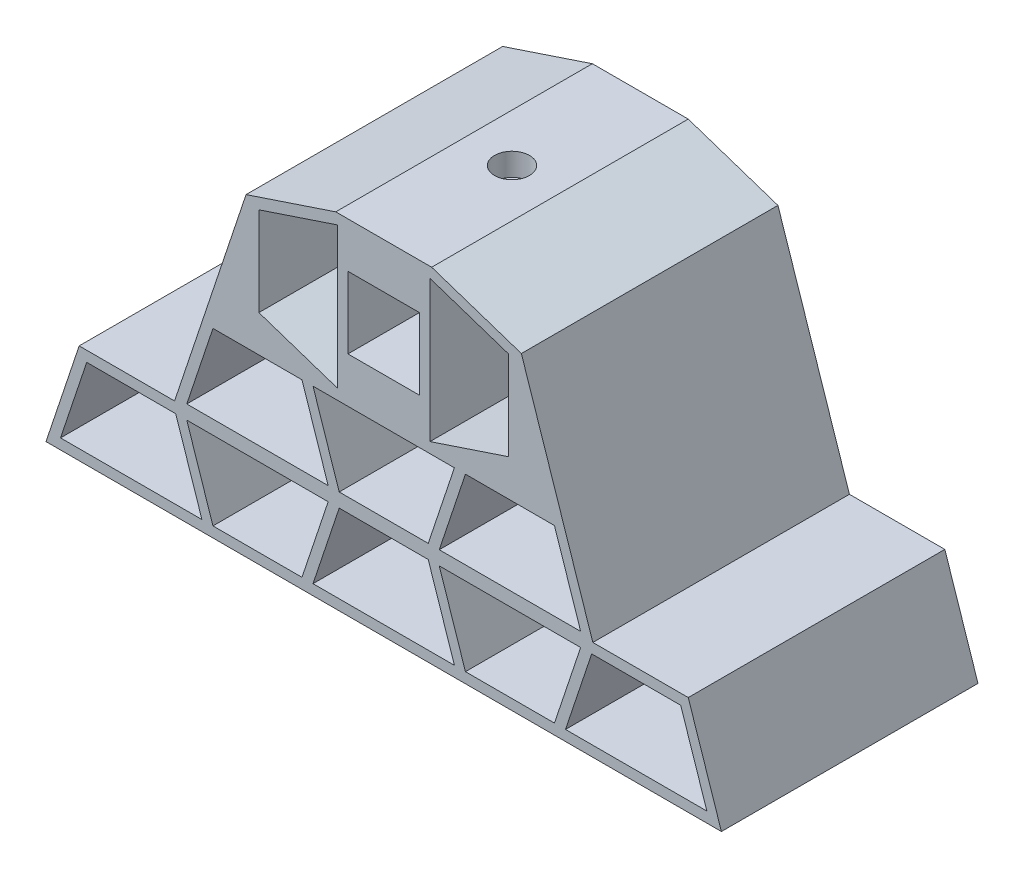
SolidWorks part; units mm, degrees
ref_plane "Front Plane" through (0, 0, 0) normal (0, 0, 1) x (1, 0, 0)
ref_plane "Top Plane" through (0, 0, 0) normal (0, 1, 0) x (1, 0, 0)
ref_plane "Right Plane" through (0, 0, 0) normal (1, 0, 0) x (0, 0, -1)
sketch "Sketch1" plane through (0, 0, 0) normal (0, 0, 1) x (1, 0, 0)
  line L0 (0, 37.8111) -> (0, -97.9817) construction
  line L1 (-53.0722, 0) -> (46.9222, 0) construction
  line L2 (-13.25, 20.25) -> (-13.25, -20.25)
  line L3 (-10.25, -10.25) -> (10.25, -10.25)
  line L4 (-10.25, -10.25) -> (-10.25, 10.25)
  line L5 (-10.25, 10.25) -> (10.25, 10.25)
  line L6 (10.25, -10.25) -> (10.25, 10.25)
  line L7 (-10.25, -10.25) -> (10.25, 10.25) construction
  line L8 (-10.25, 10.25) -> (10.25, -10.25) construction
  line L9 (-13.25, 20.25) -> (-35.75, 12.75)
  line L10 (-35.75, 12.75) -> (-35.75, -12.75)
  line L11 (-13.25, -20.25) -> (-35.75, -12.75)
  line L12 (13.25, -20.25) -> (35.75, -12.75)
  line L13 (35.75, 12.75) -> (35.75, -12.75)
  line L14 (13.25, 20.25) -> (35.75, 12.75)
  line L15 (13.25, 20.25) -> (13.25, -20.25)
  line L31 (-87.2368, -46.75) -> (-59.9079, -46.75)
  line L32 (-99.4186, -49.75) -> (117.8483, -49.75) construction
  line L45 (-12.75, -49.75) -> (12.75, -49.75)
  line L46 (12.75, -49.75) -> (20.25, -72.25)
  line L47 (20.25, -72.25) -> (-20.25, -72.25)
  line L48 (-20.25, -72.25) -> (-12.75, -49.75)
  line L49 (15.9123, -49.75) -> (23.4123, -72.25)
  line L50 (23.4123, -72.25) -> (48.9123, -72.25)
  line L51 (48.9123, -72.25) -> (56.4123, -49.75)
  line L52 (56.4123, -49.75) -> (15.9123, -49.75)
  line L53 (-48.9123, -72.25) -> (-56.4123, -49.75)
  line L54 (-23.4123, -72.25) -> (-48.9123, -72.25)
  line L55 (-15.9123, -49.75) -> (-23.4123, -72.25)
  line L56 (-56.4123, -49.75) -> (-15.9123, -49.75)
  line L57 (59.5746, -49.75) -> (52.0746, -72.25)
  line L58 (52.0746, -72.25) -> (92.5746, -72.25)
  line L59 (92.5746, -72.25) -> (85.0746, -49.75)
  line L60 (85.0746, -49.75) -> (59.5746, -49.75)
  line L61 (-92.5746, -72.25) -> (-85.0746, -49.75)
  line L62 (-52.0746, -72.25) -> (-92.5746, -72.25)
  line L63 (-59.5746, -49.75) -> (-52.0746, -72.25)
  line L64 (-85.0746, -49.75) -> (-59.5746, -49.75)
  line L65 (96.7368, -75.25) -> (-96.7368, -75.25)
  line L66 (-96.7368, -75.25) -> (-87.2368, -46.75)
  line L67 (-59.9079, -46.75) -> (-39.4293, 14.6859)
  line L68 (-13.7368, 23.25) -> (13.7368, 23.25)
  line L69 (-39.4293, 14.6859) -> (-13.7368, 23.25)
  line L70 (-70.1634, -47.75) -> (102.7428, -47.75) construction
  line L71 (48.9123, -23.25) -> (56.4123, -45.75)
  line L72 (23.4123, -23.25) -> (48.9123, -23.25)
  line L73 (15.9123, -45.75) -> (23.4123, -23.25)
  line L74 (56.4123, -45.75) -> (15.9123, -45.75)
  line L75 (20.25, -23.25) -> (-20.25, -23.25)
  line L76 (12.75, -45.75) -> (20.25, -23.25)
  line L77 (-12.75, -45.75) -> (12.75, -45.75)
  line L78 (-20.25, -23.25) -> (-12.75, -45.75)
  line L79 (-23.4123, -23.25) -> (-48.9123, -23.25)
  line L80 (-15.9123, -45.75) -> (-23.4123, -23.25)
  line L81 (-56.4123, -45.75) -> (-15.9123, -45.75)
  line L82 (-48.9123, -23.25) -> (-56.4123, -45.75)
  line L83 (96.7368, -75.25) -> (87.2368, -46.75)
  line L84 (87.2368, -46.75) -> (59.9079, -46.75)
  line L85 (59.9079, -46.75) -> (39.4293, 14.6859)
  line L86 (39.4293, 14.6859) -> (13.7368, 23.25)
  point P5 (0, 0)
  point P18 (-35.75, 0)
  point P19 (-13.25, 0)
  point P23 (13.25, 0)
  point P24 (35.75, 0)
  point P46 (16.5, -61)
  point P64 (0, -75.25)
  point P71 (0, 23.25)
  dimension "D1" = 20.5
  dimension "D2" = 20.5
  dimension "D3" = 3
  dimension "D4" = 22.5
  dimension "D5" = 12.75
  dimension "D6" = 20.25
  dimension "D7" = 2
  dimension "D8" = 3
  dimension "D9" = 3
  dimension "D10" = 3
  dimension "D11" = 13
  dimension "D20" = 40.5
  dimension "D21" = 25.5
  dimension "D22" = 22.5
  dimension "D23" = 12.75
  dimension "D24" = 20.25
  dimension "D25" = 25.5
  dimension "D26" = 40.5
  dimension "D27" = 22.5
  dimension "D28" = 3
  dimension "D29" = 40.5
  dimension "D30" = 25.5
  dimension "D31" = 22.5
  dimension "D32" = 3
  dimension "D33" = 3
  dimension "D36" = 3
  dimension "D37" = 3
extrude "Boss-Extrude1" add sketch "Sketch1" along normal blind 73.5
sketch "Sketch2" plane through (0, 23.25, 0) normal (0, 1, 0) x (1, 0, 0)
  line L0 (0, 29.916) -> (0, -88.6772) construction
  circle A0 centre (0, -36.75) radius 2.75
  dimension "D1" = 5.5
  dimension "D2" = 36.75
extrude "Cut-Extrude1" cut sketch "Sketch2" against normal up to surface (33.5 mm away) up to face at (0, -10.25, 36.75)
sketch "Sketch3" plane through (0, 23.25, 0) normal (0, 1, 0) x (1, 0, 0)
  circle A0 centre (0, -36.75) radius 5
  dimension "D1" = 10
extrude "Cut-Extrude2" cut sketch "Sketch3" against normal blind 6.5
